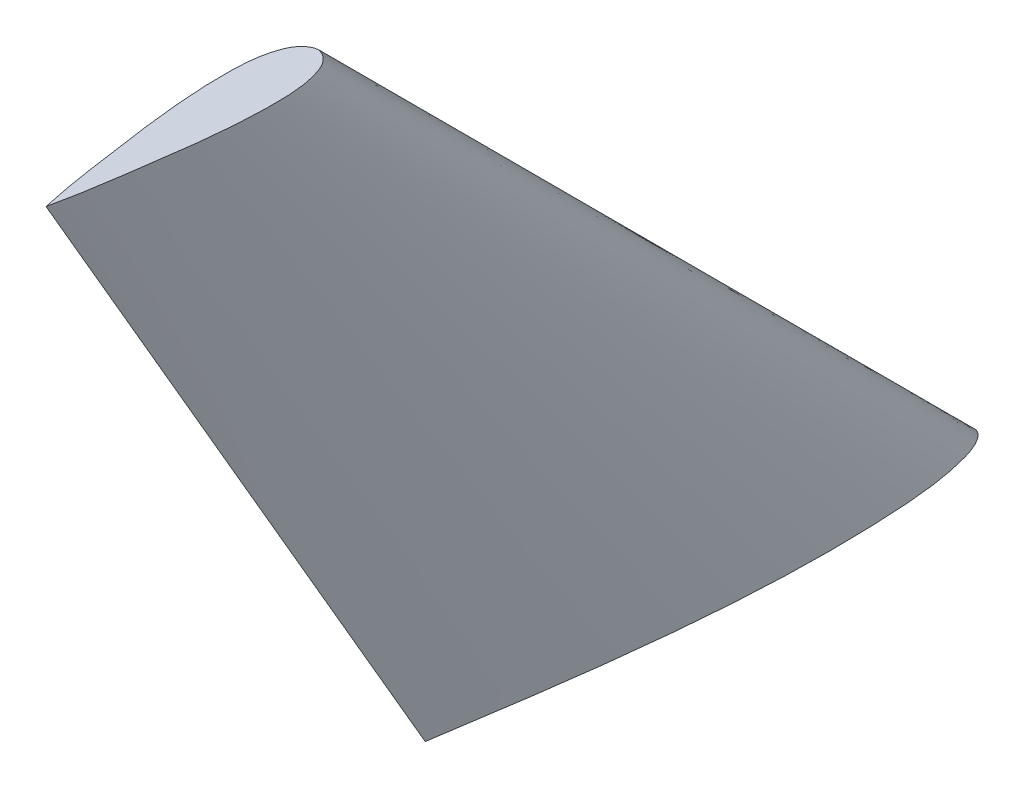
SolidWorks part; units mm, degrees
ref_plane "Front Plane" through (0, 0, 0) normal (0, 0, 1) x (1, 0, 0)
ref_plane "Top Plane" through (0, 0, 0) normal (0, 1, 0) x (1, 0, 0)
ref_plane "Right Plane" through (0, 0, 0) normal (1, 0, 0) x (0, 0, -1)
sketch "Sketch1" plane through (0, 0, 0) normal (0, 1, 0) x (1, 0, 0)
  line L0 (-215.8823, 1347.3324) -> (-486.544, 1347.3324) construction
  line L1 (0, -2697.1219) -> (0, 2697.1219) construction
  line L2 (-309.7777, -14582.8325) -> (-309.7777, -14310.2464) construction
  line L3 (423.7023, 3204.6344) -> (423.7023, 3740.6344) construction
  spline S0 degree 3 poles (0, 2697.1219) (42.9784, 2725.486) (108.3848, 2684.8628) (190.0046, 2564.3753) (245.7689, 2389.6213) (322.3373, 2034.395) (456.0027, 327.1899) (218.3518, -1297.3766) (0, -2697.1219) knots 0 0 0 0 0.021686 0.037601 0.078636 0.11926 0.234393 1 1 1 1
  spline S1 degree 3 poles (0, 2697.1219) (-42.9784, 2725.486) (-108.3848, 2684.8628) (-190.0046, 2564.3753) (-245.7689, 2389.6213) (-322.3373, 2034.395) (-456.0027, 327.1899) (-218.3518, -1297.3766) (0, -2697.1219) knots 0 0 0 0 0.021686 0.037601 0.078636 0.11926 0.234393 1 1 1 1
  point P6 (0, 0)
  dimension "D1" = 5394.2437
sketch "Sketch2" plane through (0, 0, 0) normal (1, 0, 0) x (0, 0, -1)
  line L0 (2743.6321, 0) -> (-3759.047, 6473.0925) construction
  line L1 (-2697.1219, 0) -> (2697.1219, 0) construction
  line L2 (-2650.6117, 0) -> (-6456.1689, 6473.0925) construction
  line L3 (-6456.1689, 6473.0925) -> (-3759.047, 6473.0925) construction
  line L4 (1395.0711, 0) -> (-4433.3275, 6473.0925) construction
  line L5 (1298.5924, 1438.4649) -> (99.8715, 1438.4649) construction
  line L6 (99.8715, 1438.4649) -> (-3496.291, 1438.4649) construction
  line L7 (99.8715, 1438.4649) -> (99.8715, 0) construction
  line L8 (1395.0711, 0) -> (1395.0711, 8848.7147) construction
  line L9 (1395.0711, 0) -> (1395.0711, -1905) construction
  dimension "D1" = 1348.5609
  dimension "D2" = 5394.2437
  dimension "D3" = 2697.1219
  dimension "D4" = 674.2805
  dimension "D5" = 6473.0925
  dimension "D6" = 1438.4649
  dimension "D7" = 42
  dimension "D8" = 1905
ref_plane "Plane1" through (0, 6473.0925, 0) normal (0, 1, 0) x (1, 0, 0)
sketch "Sketch3" plane through (0, 6473.0925, 0) normal (0, 1, 0) x (1, 0, 0)
  line L0 (0, -3759.047) -> (0, -6456.1689) construction
  line L1 (1.5245, -5940.7532) -> (-755.8625, -5716.5827) construction
  spline S0 degree 3 poles (0, -3759.047) (117.183, -3780.2351) (232.2489, -4018.3163) (275.3296, -4692.0995) (156.1442, -5521.403) (56.5382, -6207.3318) (0, -6456.1689) knots 0 0 0 0 0.115122 0.255728 0.727828 1 1 1 1
  spline S1 degree 3 poles (0, -3759.047) (-117.183, -3780.2351) (-232.2489, -4018.3163) (-275.3296, -4692.0995) (-156.1442, -5521.403) (-56.5382, -6207.3318) (0, -6456.1689) knots 0 0 0 0 0.115122 0.255728 0.727828 1 1 1 1
loft "Loft2" add profiles "Sketch1", "Sketch3"
equation "\"D1@Sketch2\"=.25*\"D2@Sketch2\""
equation "\"D4@Sketch2\"=.25*\"D3@Sketch2\""
